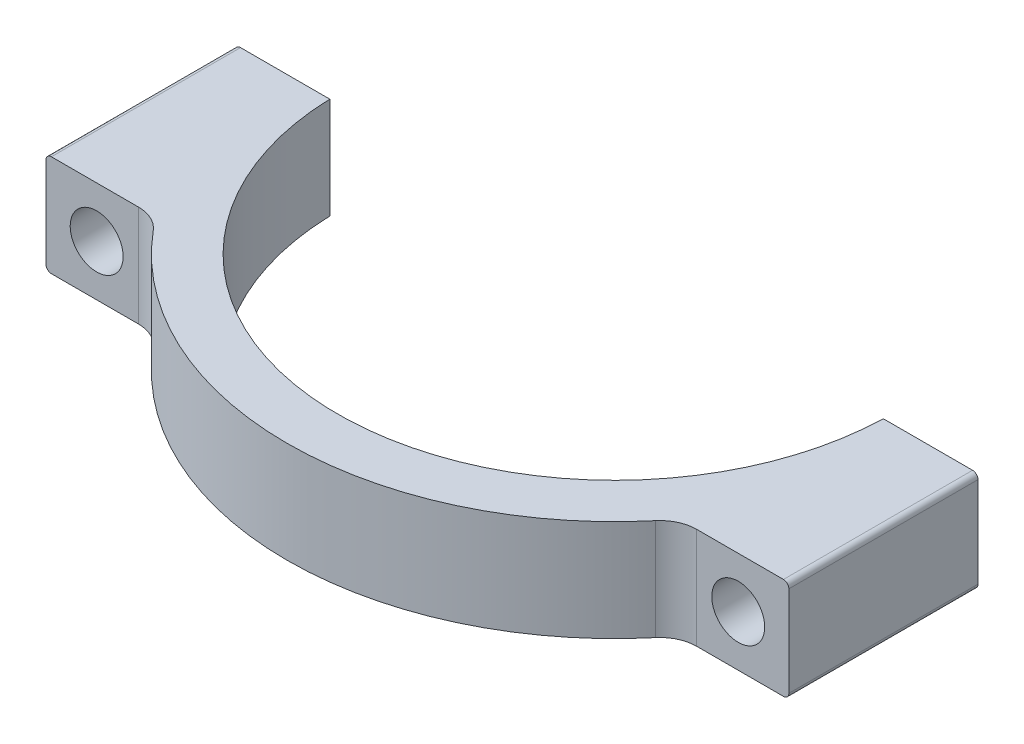
SolidWorks part; units mm, degrees
material "6061-T6 (SS)"
ref_plane "Front Plane" through (0, 0, 0) normal (0, 0, 1) x (1, 0, 0)
ref_plane "Top Plane" through (0, 0, 0) normal (0, 1, 0) x (1, 0, 0)
ref_plane "Right Plane" through (0, 0, 0) normal (1, 0, 0) x (0, 0, -1)
sketch "Sketch1" plane through (0, 0, 0) normal (0, 1, 0) x (1, 0, 0)
  line L0 (-26.0238, 30.0355) -> (-34.925, 30.0355)
  line L1 (-34.925, 30.0355) -> (-34.925, 0)
  line L2 (-34.925, 0) -> (34.925, 0)
  line L3 (34.925, 0) -> (34.925, 30.0355)
  line L4 (34.925, 30.0355) -> (26.0238, 30.0355)
  arc A0 (-26.0238, 30.0355) -> (26.0238, 30.0355) centre (0, 30.7975) ccw
  dimension "D1" = 52.07
  dimension "D3" = 4.7625
  dimension "D2" = 0.762
  dimension "D4" = 69.85
  dimension "D5" = 8.9012
extrude "Boss-Extrude1" add sketch "Sketch1" along normal mid plane 9.525
hole_wizard "#10 Clearance Hole1" positions "Sketch2" profile "Sketch3" hole size "#10" standard "ANSI Inch" end condition through all
sketch "Sketch2" plane through (0, 0, -30.0355) normal (0, 0, -1) x (-1, 0, 0)
  line L0 (-30.1625, 0) -> (0, 0)
  line L1 (0, 0) -> (30.1625, 0)
  point P0 (-30.1625, 0)
  point P2 (30.1625, 0)
  dimension "D1" = 60.325
sketch "Sketch3" plane through (30.1625, 0, -30.0355) normal (1, 0, 0) x (0, 1, 0)
  line L0 (0, 0) -> (0, 30.0355)
  line L1 (0, 30.0355) -> (2.4892, 30.0355)
  line L2 (2.4892, 30.0355) -> (2.4892, 0)
  line L5 (2.4892, 0) -> (0, 0)
  line L11 (0, -6.35) -> (0, 107.95) construction
  dimension "Thru Hole Dia." = 4.9784
  dimension "Thru Hole Depth" = 30.0355
sketch "Sketch6" plane through (0, -4.7625, 0) normal (0, -1, 0) x (1, 0, 0)
  line L0 (-24.5902, -12.2555) -> (-34.925, -12.2555)
  line L1 (-34.925, -30.0355) -> (-34.925, 0) construction
  line L2 (-34.925, -12.2555) -> (-34.925, 0)
  line L3 (-34.925, 0) -> (0, 0)
  line L7 (-26.0238, -30.0355) -> (-34.925, -30.0355) construction
  arc A0 (0, 0) -> (-24.5902, -12.2555) centre (0, -30.7975) ccw
  dimension "D1" = 17.78
extrude "Cut-Extrude2" cut sketch "Sketch6" against normal through all
mirror "Mirror1" about plane through (0, 0, 0) normal (1, 0, 0) of "Cut-Extrude2"
fillet "Fillet1" radius 3.429 2 edges at (24.5902, 0, -12.2555) (-24.5902, 0, -12.2555)
fillet "Fillet2" radius 0.508 4 edges at (-34.925, 4.7625, -21.1455) (-34.925, -4.7625, -21.1455) (34.925, 4.7625, -21.1455) (34.925, -4.7625, -21.1455)
